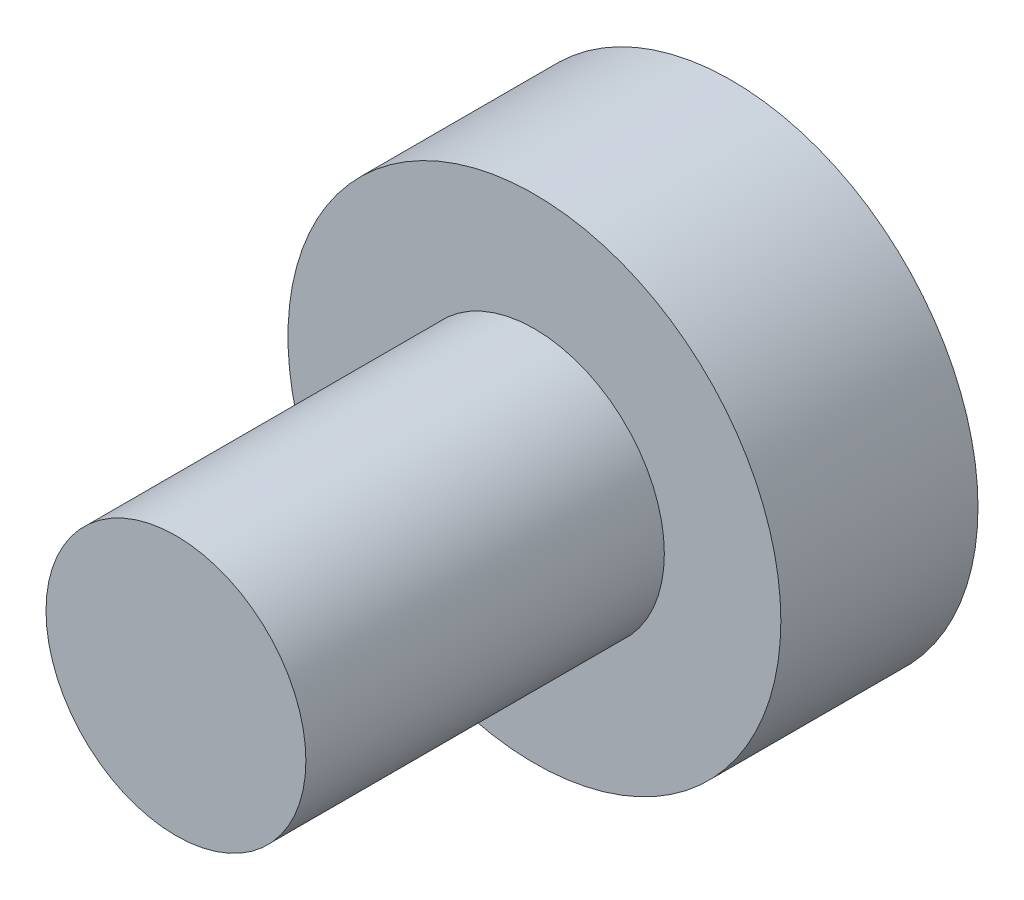
SolidWorks part; units mm, degrees
material "Brass"
ref_plane "Front Plane" through (0, 0, 0) normal (0, 0, 1) x (1, 0, 0)
ref_plane "Top Plane" through (0, 0, 0) normal (0, 1, 0) x (1, 0, 0)
ref_plane "Right Plane" through (0, 0, 0) normal (1, 0, 0) x (0, 0, -1)
sketch "Sketch1" plane through (0, 0, 0) normal (0, 0, 1) x (1, 0, 0)
  circle A0 centre (0, 0) radius 2.75
  dimension "D1" = 5.5
extrude "Boss-Extrude1" add sketch "Sketch1" along normal blind 2.2 from offset 2.2
sketch "Sketch2" plane through (0, 0, 0) normal (0, 0, 1) x (1, 0, 0)
  circle A0 centre (0, 0) radius 1.45
  dimension "D1" = 2.9
extrude "Boss-Extrude2" add sketch "Sketch2" along normal blind 4 from offset 0
